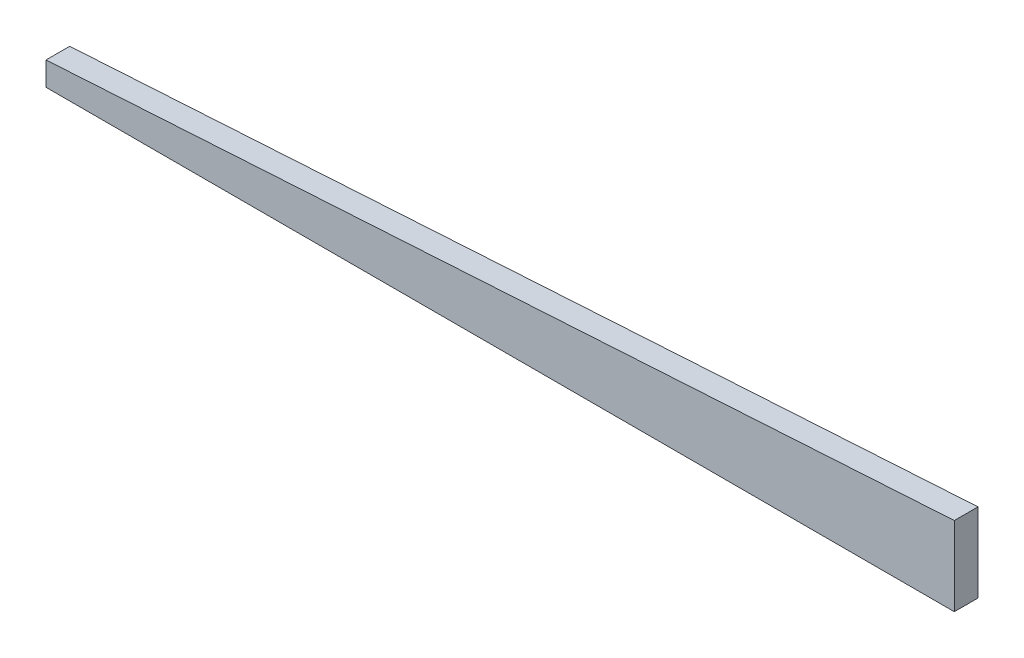
SolidWorks part; units mm, degrees
ref_plane "Front Plane" through (0, 0, 0) normal (0, 0, 1) x (1, 0, 0)
ref_plane "Top Plane" through (0, 0, 0) normal (0, 1, 0) x (1, 0, 0)
ref_plane "Right Plane" through (0, 0, 0) normal (1, 0, 0) x (0, 0, -1)
sketch "Sketch1" plane through (0, 0, 0) normal (0, 0, 1) x (1, 0, 0)
  line L0 (0, 0) -> (-115, 0)
  line L1 (-115, 0) -> (-115, 3)
  line L2 (-115, 3) -> (0, 10)
  line L3 (0, 10) -> (0, 0)
  dimension "D1" = 10
  dimension "D2" = 115
  dimension "D3" = 3
extrude "Boss-Extrude1" add sketch "Sketch1" along normal blind 3
